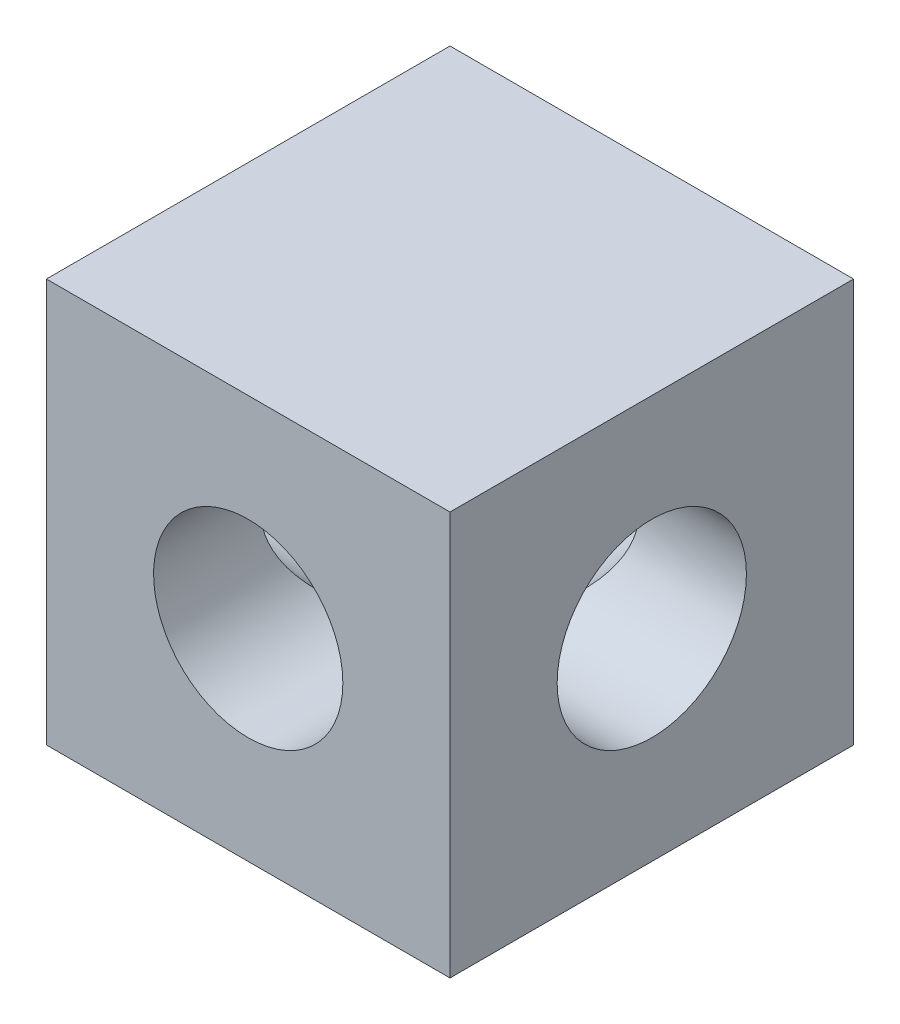
SolidWorks part; units mm, degrees
ref_plane "Front Plane" through (0, 0, 0) normal (0, 0, 1) x (1, 0, 0)
ref_plane "Top Plane" through (0, 0, 0) normal (0, 1, 0) x (1, 0, 0)
ref_plane "Right Plane" through (0, 0, 0) normal (1, 0, 0) x (0, 0, -1)
sketch "Sketch1" plane through (0, 0, 0) normal (0, 0, 1) x (1, 0, 0)
  line L1 (-10.16, -10.16) -> (10.16, -10.16)
  line L2 (-10.16, -10.16) -> (-10.16, 10.16)
  line L3 (-10.16, 10.16) -> (10.16, 10.16)
  line L4 (10.16, -10.16) -> (10.16, 10.16)
  line L5 (-10.16, -10.16) -> (10.16, 10.16) construction
  line L6 (-10.16, 10.16) -> (10.16, -10.16) construction
  circle A0 centre (0, 0) radius 4.765
  point P0 (0, 0)
  dimension "D3" = 9.53
  dimension "D1" = 20.32
  dimension "D2" = 20.32
extrude "Boss-Extrude1" add sketch "Sketch1" along normal blind 20.32
sketch "Sketch2" plane through (0, 0, 10.16) normal (1, 0, 0) x (0, 0, -1)
  line L0 (-10.16, -10.16) -> (-10.16, 10.16) construction
  line L1 (-10.16, -10.16) -> (10.16, -10.16)
  line L2 (-10.16, -10.16) -> (-10.16, 10.16)
  line L3 (-10.16, 10.16) -> (10.16, 10.16)
  line L4 (10.16, -10.16) -> (10.16, 10.16)
  line L5 (-10.16, -10.16) -> (10.16, 10.16) construction
  line L6 (-10.16, 10.16) -> (10.16, -10.16) construction
  line L7 (-10.16, 10.16) -> (10.16, 10.16) construction
  circle A0 centre (0, 0) radius 4.765
  point P0 (0, 0)
  dimension "D1" = 10.16
  dimension "D2" = 10.16
extrude "Cut-Extrude1" cut sketch "Sketch2" against normal through all both and the other way through all contours A0
